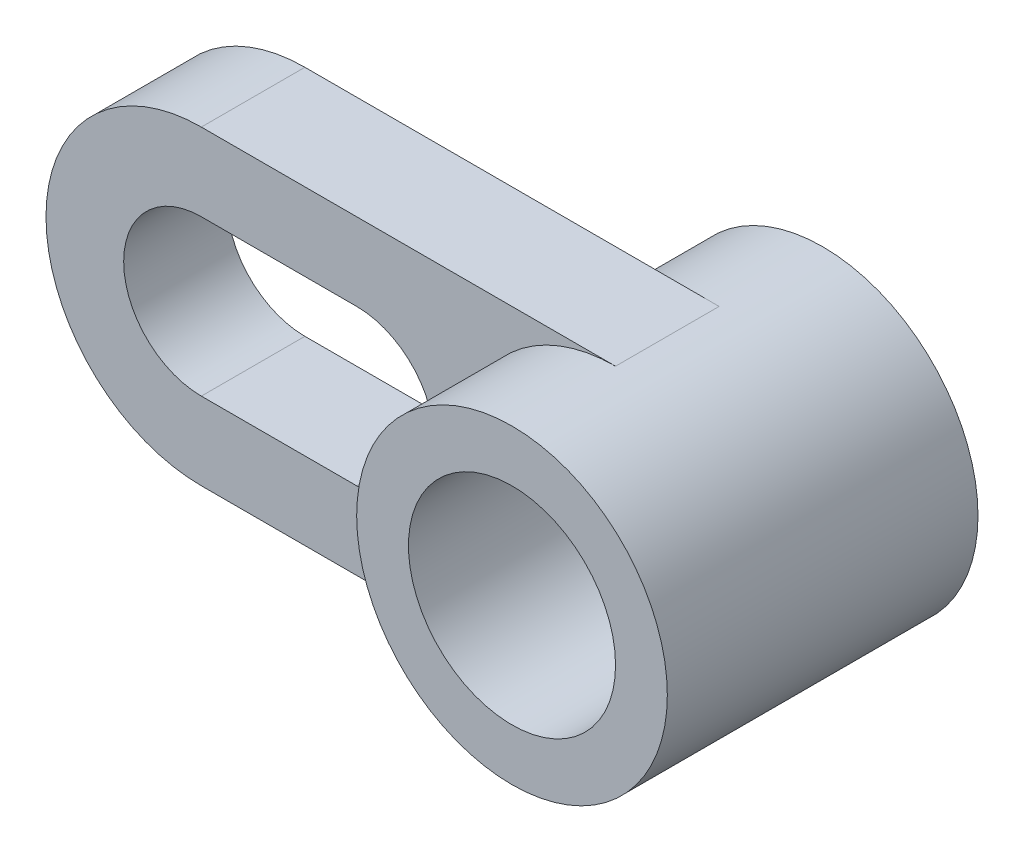
SolidWorks part; units mm, degrees
ref_plane "Front Plane" through (0, 0, 0) normal (0, 0, 1) x (1, 0, 0)
ref_plane "Top Plane" through (0, 0, 0) normal (0, 1, 0) x (1, 0, 0)
ref_plane "Right Plane" through (0, 0, 0) normal (1, 0, 0) x (0, 0, -1)
sketch "Sketch1" plane through (0, 0, 0) normal (0, 0, 1) x (1, 0, 0)
  circle A0 centre (0, 0) radius 15
  circle A1 centre (0, 0) radius 10
  dimension "D1" = 20
  dimension "D2" = 30
extrude "Boss-Extrude1" add sketch "Sketch1" against normal blind 30
ref_plane "Plane1" through (0, 0, -15) normal (0, 0, 1) x (1, 0, 0)
sketch "Sketch2" plane through (0, 0, -15) normal (0, 0, 1) x (1, 0, 0)
  line L0 (-40, 0) -> (-25, 0) construction
  line L3 (-40, 7.5) -> (-25, 7.5)
  line L6 (-40, -7.5) -> (-25, -7.5)
  line L7 (-40, 0) -> (0, 0) construction
  line L10 (-40, 15) -> (0, 15)
  line L11 (-40, -15) -> (0, -15)
  arc A4 (-40, 7.5) -> (-40, -7.5) centre (-40, 0) ccw
  arc A5 (-25, -7.5) -> (-25, 7.5) centre (-25, 0) ccw
  arc A9 (-40, 15) -> (-40, -15) centre (-40, 0) ccw
  arc A11 (0, 15) -> (0, -15) centre (0, 0) ccw
  point P3 (-32.5, 0)
  point P9 (-20, 0)
  dimension "D1" = 30
  dimension "D2" = 15
  dimension "D3" = 25
  dimension "D4" = 15
extrude "Boss-Extrude2" add sketch "Sketch2" along normal mid plane 10
